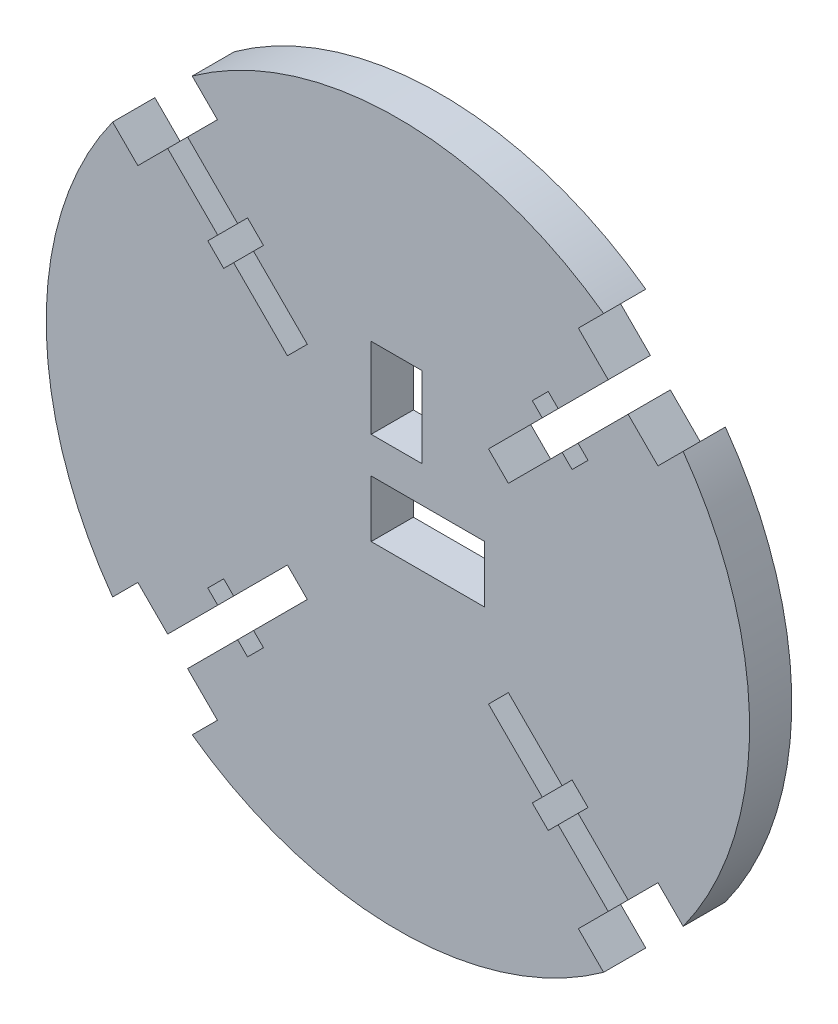
SolidWorks part; units mm, degrees
ref_plane "Plan de face" through (0, 0, 0) normal (0, 0, 1) x (1, 0, 0)
ref_plane "Plan de dessus" through (0, 0, 0) normal (0, 1, 0) x (1, 0, 0)
ref_plane "Plan de droite" through (0, 0, 0) normal (1, 0, 0) x (0, 0, -1)
sketch "Esquisse1" plane through (0, 0, 0) normal (0, 0, 1) x (1, 0, 0)
  line L0 (-125, 0) -> (125, 0) construction
  line L1 (0, 125) -> (0, -125) construction
  line L2 (-88.3883, -88.3883) -> (88.3883, 88.3883) construction
  line L3 (-88.3883, 88.3883) -> (88.3883, -88.3883) construction
  line L4 (0, 0) -> (-88.3883, -88.3883) construction
  line L5 (88.3883, 88.3883) -> (-88.3883, 88.3883) construction
  line L6 (-9.5, 10.1) -> (30.7, 10.1)
  line L7 (-9.5, 10.1) -> (-9.5, -10.1)
  line L8 (-9.5, -10.1) -> (30.7, -10.1)
  line L9 (30.7, 10.1) -> (30.7, -10.1)
  line L10 (-9.5, 10.1) -> (30.7, -10.1) construction
  line L11 (-9.5, -10.1) -> (30.7, 10.1) construction
  line L12 (-9.5, 10.1) -> (-9.5, 62.7767) construction
  line L13 (-9.5, 51.5508) -> (-9.5, 22.9136)
  line L14 (-9.5, 51.5508) -> (8.6239, 51.5508)
  line L15 (-9.5, 22.9136) -> (8.6239, 22.9136)
  line L16 (8.6239, 51.5508) -> (8.6239, 22.9136)
  circle A0 centre (0, 0) radius 125
  point P9 (10.6, 0)
  dimension "D1" = 250
  dimension "D2" = 45
  dimension "D3" = 45
  dimension "D4" = 40.2
  dimension "D5" = 20.2
  dimension "D6" = 30.7
  dimension "D7" = 10.1
extrude "Boss.-Extru.1" add sketch "Esquisse1" along normal blind 15
sketch "Esquisse3" plane through (0, 0, 15) normal (0, 0, 1) x (1, 0, 0)
  line L0 (0, 125) -> (0, -125) construction
  line L1 (125, 0) -> (-125, 0) construction
  line L2 (-88.3883, 88.3883) -> (88.3883, -88.3883) construction
  line L3 (88.3883, 88.3883) -> (-88.3883, -88.3883) construction
  line L5 (112.6282, -84.3439) -> (92.4328, -64.1485)
  line L6 (112.6282, -84.3439) -> (84.3439, -112.6282)
  line L7 (84.3439, -112.6282) -> (64.1485, -92.4328)
  line L8 (92.4328, -64.1485) -> (64.1485, -92.4328)
  line L9 (112.6282, -84.3439) -> (64.1485, -92.4328) construction
  line L10 (84.3439, -112.6282) -> (92.4328, -64.1485) construction
  line L11 (81.9503, -89.0214) -> (89.0214, -81.9503)
  line L12 (81.9503, -89.0214) -> (32.2003, -39.2714)
  line L13 (32.2003, -39.2714) -> (39.2714, -32.2003)
  line L14 (89.0214, -81.9503) -> (39.2714, -32.2003)
  line L15 (81.9503, -89.0214) -> (39.2714, -32.2003) construction
  line L16 (32.2003, -39.2714) -> (89.0214, -81.9503) construction
  line L17 (53.4317, -67.5738) -> (67.5738, -53.4317)
  line L18 (53.4317, -67.5738) -> (47.7748, -61.917)
  line L19 (47.7748, -61.917) -> (61.917, -47.7748)
  line L20 (67.5738, -53.4317) -> (61.917, -47.7748)
  line L21 (53.4317, -67.5738) -> (61.917, -47.7748) construction
  line L22 (47.7748, -61.917) -> (67.5738, -53.4317) construction
  circle A0 centre (0, 0) radius 125 construction
  point P11 (88.3883, -88.3883)
  point P17 (60.6108, -60.6108)
  point P22 (57.6743, -57.6743)
  dimension "D1" = 45
  dimension "D2" = 45
  dimension "D3" = 40
  dimension "D4" = 10
  dimension "D5" = 20
  dimension "D6" = 8
extrude "Enlèv. mat.-Extru.1" cut sketch "Esquisse3" against normal blind 15 contours L12 L13 L14 L11 | L17 L20 L19 L18 | L8 L7 L6 L5
pattern_circular "Répétition circulaire1" count 4 every 90 about axis through (0, 0, 0) along (0, 0, 1) of "Enlèv. mat.-Extru.1"
